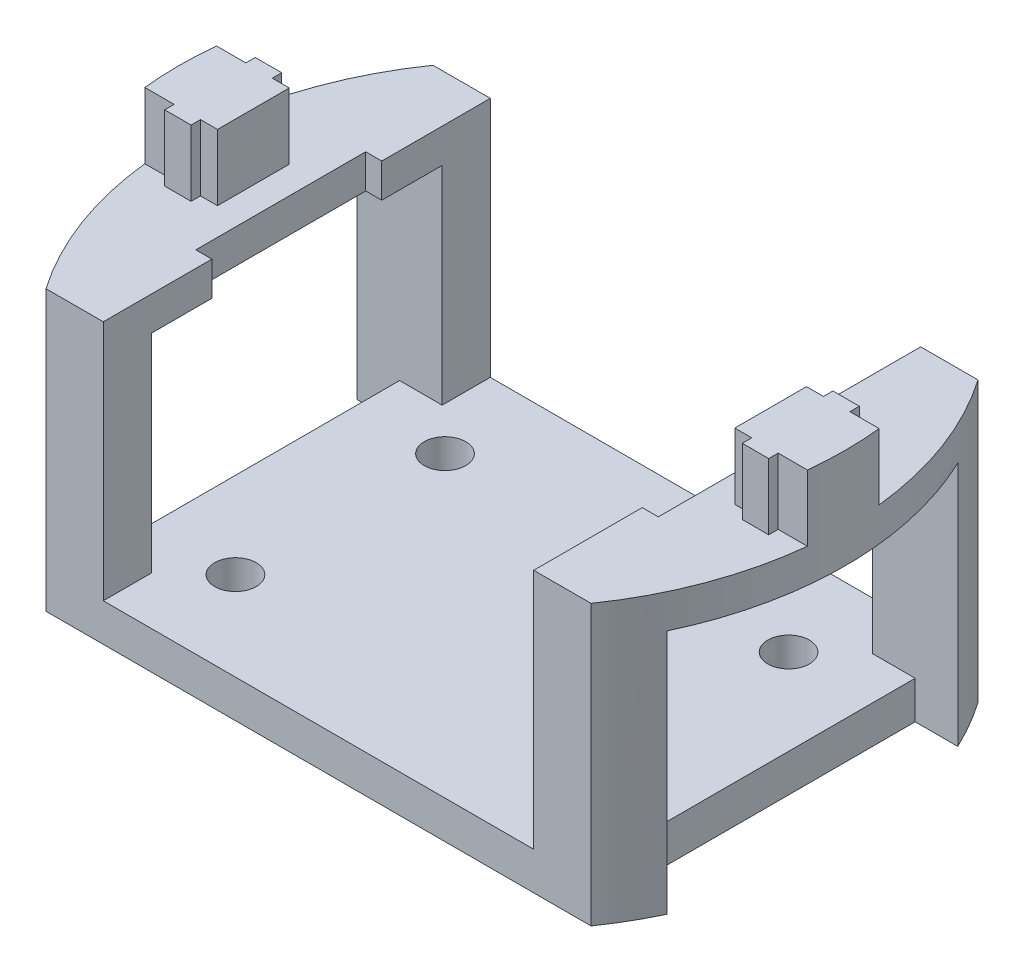
SolidWorks part; units mm, degrees
ref_plane "Alzado" through (0, 0, 0) normal (0, 0, 1) x (1, 0, 0)
ref_plane "Planta" through (0, 0, 0) normal (0, 1, 0) x (1, 0, 0)
ref_plane "Vista lateral" through (0, 0, 0) normal (1, 0, 0) x (0, 0, -1)
sketch "Croquis1" plane through (0, 0, 0) normal (0, 1, 0) x (1, 0, 0)
  line L0 (0, -39.9983) -> (0, 39.9983) construction
  line L1 (-13.935, -10.25) -> (13.935, -10.25)
  line L3 (-13.935, 10.25) -> (13.935, 10.25)
  line L5 (-13.935, -10.25) -> (13.935, 10.25) construction
  line L6 (-13.935, 10.25) -> (13.935, -10.25) construction
  arc A0 (-13.935, 10.25) -> (-13.935, -10.25) centre (0.8007, 0) ccw
  arc A1 (13.935, 10.25) -> (13.935, -10.25) centre (-0.8007, 0) cw
  point P0 (0, 0)
  dimension "D3" = 17.95
  dimension "D1" = 27.87
  dimension "D2" = 20.5
extrude "Saliente-Extruir1" add sketch "Croquis1" along normal blind 14.8
sketch "Croquis2" plane through (0, 0, 0) normal (1, 0, 0) x (0, 0, -1)
  line L0 (-7.7, 14.8) -> (-7.7, 13) construction
  line L1 (10.25, 14.8) -> (-10.25, 14.8) construction
  line L2 (-10.25, 14.8) -> (-10.25, 0) construction
  line L3 (7.7, 0) -> (7.7, 2) construction
  line L4 (-10.25, 0) -> (10.25, 0) construction
  line L5 (10.25, 14.8) -> (10.25, 0) construction
  line L7 (-7.7, 13) -> (7.7, 13)
  line L8 (-7.7, 13) -> (-7.7, 2)
  line L9 (-7.7, 2) -> (7.7, 2)
  line L10 (7.7, 13) -> (7.7, 2)
  dimension "D1" = 1.8
  dimension "D2" = 2.55
  dimension "D3" = 2
  dimension "D4" = 2.55
extrude "Cortar-Extruir1" cut sketch "Croquis2" against normal through all both and the other way through all
sketch "Croquis3" plane through (0, 14.8, 0) normal (0, 1, 0) x (1, 0, 0)
  line L0 (13.935, 10.25) -> (-13.935, 10.25) construction
  line L1 (10.9, -10.25) -> (-10.9, -10.25)
  line L2 (10.9, -10.25) -> (10.9, -4.5)
  line L3 (10.9, 10.25) -> (-10.9, 10.25)
  line L4 (-10.9, -10.25) -> (-10.9, -4.5)
  line L5 (10.9, -10.25) -> (-10.9, 10.25) construction
  line L6 (10.9, 10.25) -> (-10.9, -10.25) construction
  line L7 (11.75, 0) -> (-11.75, 0) construction
  line L8 (-11.75, 4.5) -> (-11.75, -4.5)
  line L9 (-11.75, 4.5) -> (-10.9, 4.5)
  line L10 (-11.75, -4.5) -> (-10.9, -4.5)
  line L11 (-10.9, 4.5) -> (-10.9, 10.25)
  line L12 (0, -8.14) -> (0, 8.14) construction
  line L13 (11.75, -4.5) -> (10.9, -4.5)
  line L14 (11.75, 4.5) -> (10.9, 4.5)
  line L15 (11.75, 4.5) -> (11.75, -4.5)
  line L16 (10.9, 4.5) -> (10.9, 10.25)
  point P0 (0, 0)
  point P11 (0, 0)
  point P14 (-11.75, 0)
  point P22 (11.75, 0)
  dimension "D1" = 21.8
  dimension "D2" = 23.5
  dimension "D3" = 9
extrude "Cortar-Extruir2" cut sketch "Croquis3" against normal up to surface and the other way through all up to face at (0, 2, 0)
sketch "Croquis4" plane through (0, 14.8, 0) normal (0, 1, 0) x (1, 0, 0)
  line L0 (-11.75, 0) -> (-13.2, 0) construction
  line L1 (-11.75, -4.5) -> (-11.75, 4.5) construction
  line L2 (-13.2, 1.9) -> (-13.2, -1.9)
  line L3 (-13.2, 1.9) -> (-14.1, 1.9)
  line L4 (-14.1, 1.9) -> (-14.1, 2.4)
  line L5 (-14.1, 2.4) -> (-15.5, 2.4)
  line L6 (-15.5, 2.4) -> (-15.5, 1.9)
  line L7 (-15.5, 1.9) -> (-17.0485, 1.9)
  line L8 (-8.14, 0) -> (8.14, 0) construction
  line L9 (-15.5, -1.9) -> (-17.0485, -1.9)
  line L10 (-13.2, -1.9) -> (-14.1, -1.9)
  line L11 (-15.5, -2.4) -> (-15.5, -1.9)
  line L12 (-14.1, -2.4) -> (-15.5, -2.4)
  line L13 (-14.1, -1.9) -> (-14.1, -2.4)
  arc A0 (-13.935, 10.25) -> (-13.935, -10.25) centre (0.8007, 0) ccw construction
  arc A1 (-17.0485, 1.9) -> (-17.0485, -1.9) centre (0.8007, 0) ccw
  point P8 (-13.2, 0)
  dimension "D1" = 1.45
  dimension "D2" = 3.8
  dimension "D3" = 0.5
  dimension "D4" = 1.4
extrude "Saliente-Extruir2" add sketch "Croquis4" along normal blind 3.5
mirror "Simetría1" about plane through (0, 0, 0) normal (1, 0, 0) of "Saliente-Extruir2"
sketch "Croquis5" plane through (0, 2, 0) normal (0, 1, 0) x (1, 0, 0)
  line L0 (-9.7, 5.55) -> (-9.7, 10.25) construction
  line L1 (10.9, 10.25) -> (-10.9, 10.25) construction
  line L2 (8.6, -5.55) -> (-8.6, -5.55) construction
  line L3 (8.6, -5.55) -> (8.6, 5.55) construction
  line L4 (8.6, 5.55) -> (-8.6, 5.55) construction
  line L5 (-8.6, -5.55) -> (-8.6, 5.55) construction
  line L6 (8.6, -5.55) -> (-8.6, 5.55) construction
  line L7 (8.6, 5.55) -> (-8.6, -5.55) construction
  line L8 (9.7, 5.55) -> (9.7, 10.25) construction
  line L9 (0, -10.065) -> (0, 10.065) construction
  line L10 (-8.3, 6.65) -> (49991.7, 6.65) construction
  line L11 (-8.3, -6.65) -> (49991.7, -6.65) construction
  circle A0 centre (-8.6, -5.55) radius 1.1
  circle A1 centre (-8.6, 5.55) radius 1.1
  circle A2 centre (8.6, -5.55) radius 1.1
  circle A3 centre (8.6, 5.55) radius 1.1
  point P0 (0, 0)
  dimension "D3" = 2.2
  dimension "D4" = 2.2
  dimension "D5" = 13.3
  dimension "D1" = 19.4
extrude "Cortar-Extruir3" cut sketch "Croquis5" against normal through all
sketch "Croquis6" plane through (0, 2, 0) normal (0, 1, 0) x (1, 0, 0)
  line L2 (-13.157, 7.7) -> (-13.157, -7.7)
  line L3 (13.157, 7.7) -> (13.157, -7.7)
  line L10 (-15.4139, -7.7) -> (-10.9, -7.7)
  line L11 (-10.9, -7.7) -> (-10.9, -10.25)
  line L12 (-10.9, -10.25) -> (10.9, -10.25)
  line L13 (10.9, -10.25) -> (10.9, -7.7)
  line L14 (10.9, -7.7) -> (15.4139, -7.7)
  line L15 (15.4139, 7.7) -> (10.9, 7.7)
  line L16 (10.9, 7.7) -> (10.9, 10.25)
  line L17 (10.9, 10.25) -> (-10.9, 10.25)
  line L18 (-10.9, 10.25) -> (-10.9, 7.7)
  line L19 (-10.9, 7.7) -> (-15.4139, 7.7)
  line L20 (-15.4139, -7.7) -> (-13.157, -7.7)
  line L24 (13.157, -7.7) -> (15.4139, -7.7)
  line L25 (15.4139, 7.7) -> (13.157, 7.7)
  line L29 (-13.157, 7.7) -> (-15.4139, 7.7)
  arc A2 (15.4139, -7.7) -> (15.4139, 7.7) centre (-0.8007, 0) ccw
  arc A3 (-15.4139, 7.7) -> (-15.4139, -7.7) centre (0.8007, 0) ccw
  arc A4 (15.4139, -7.7) -> (15.4139, 7.7) centre (-0.8007, 0) ccw
  arc A5 (-15.4139, 7.7) -> (-15.4139, -7.7) centre (0.8007, 0) ccw
  dimension "D1" = 0
extrude "Cortar-Extruir4" cut sketch "Croquis6" against normal through all
sketch "Croquis7" plane through (0, 0, 0) normal (1, 0, 0) x (0, 0, -1)
  line L1 (13.8546, 20.2668) -> (-13.3769, 20.2668)
  line L2 (13.8546, 20.2668) -> (13.8546, -3.1428)
  line L3 (13.8546, -3.1428) -> (-13.3769, -3.1428)
  line L4 (-13.3769, 20.2668) -> (-13.3769, -3.1428)
extrude "Cortar-Extruir5" cut sketch "Croquis7" against normal through all
sketch "Croquis8" plane through (0, 0, 0) normal (-1, 0, 0) x (0, 0, 1)
  line L1 (-10.25, 2) -> (10.25, 2)
  line L2 (-10.25, 2) -> (-10.25, 0)
  line L3 (-10.25, 0) -> (10.25, 0)
  line L4 (10.25, 2) -> (10.25, 0)
extrude "Saliente-Extruir3" add sketch "Croquis8" along normal blind 0.5
ref_plane "Plano1" through (-0.5, 0, 0) normal (-1, 0, 0) x (0, 0, 1)
mirror "Simetría4" about plane through (-0.5, 0, 0) normal (-1, 0, 0) of bodies 109
